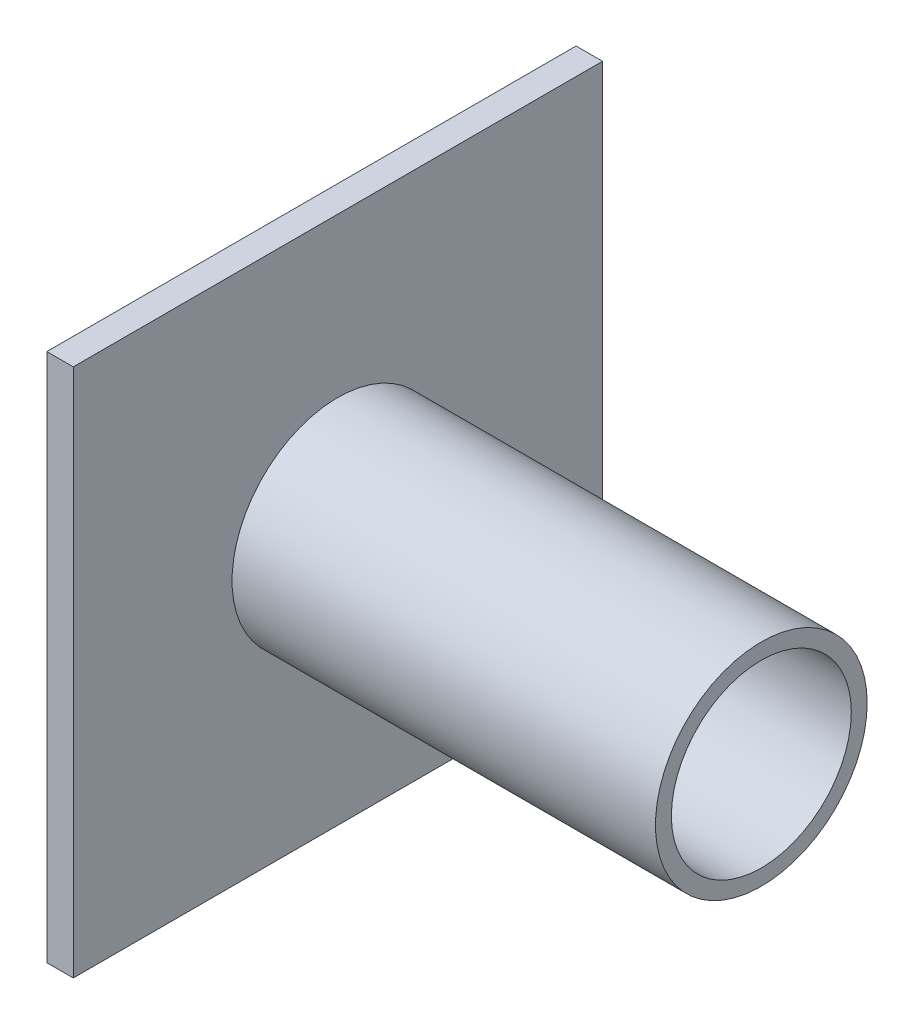
SolidWorks part; units mm, degrees
ref_plane "Front Plane" through (0, 0, 0) normal (0, 0, 1) x (1, 0, 0)
ref_plane "Top Plane" through (0, 0, 0) normal (0, 1, 0) x (1, 0, 0)
ref_plane "Right Plane" through (0, 0, 0) normal (1, 0, 0) x (0, 0, -1)
sketch "Sketch1" plane through (0, 0, 0) normal (1, 0, 0) x (0, 0, -1)
  line L1 (-50, -50) -> (50, -50)
  line L2 (-50, -50) -> (-50, 50)
  line L3 (-50, 50) -> (50, 50)
  line L4 (50, -50) -> (50, 50)
  line L5 (-50, -50) -> (50, 50) construction
  line L6 (-50, 50) -> (50, -50) construction
  point P0 (0, 0)
  dimension "D1" = 100
extrude "Boss-Extrude1" add sketch "Sketch1" along normal blind 5
sketch "Sketch2" plane through (5, 0, 0) normal (1, 0, 0) x (0, 0, -1)
  circle A0 centre (0, 0) radius 20
  dimension "D1" = 40
extrude "Boss-Extrude2" add sketch "Sketch2" along normal blind 80
shell "Shell1" thickness 3
